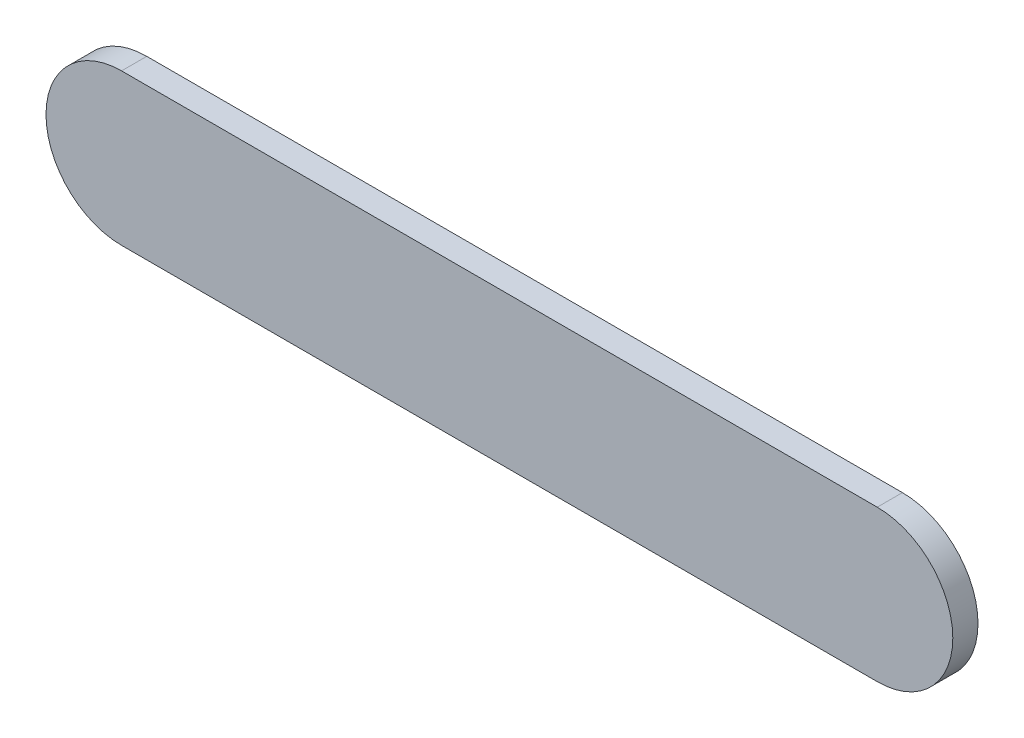
SolidWorks part; units mm, degrees
ref_plane "Front Plane" through (0, 0, 0) normal (0, 0, 1) x (1, 0, 0)
ref_plane "Top Plane" through (0, 0, 0) normal (0, 1, 0) x (1, 0, 0)
ref_plane "Right Plane" through (0, 0, 0) normal (1, 0, 0) x (0, 0, -1)
sketch "Sketch1" plane through (0, 0, 0) normal (0, 0, 1) x (1, 0, 0)
  line L0 (0, 0) -> (150, 0) construction
  line L1 (0, 15) -> (150, 15)
  line L2 (0, -15) -> (150, -15)
  arc A0 (0, 15) -> (0, -15) centre (0, 0) ccw
  arc A1 (150, -15) -> (150, 15) centre (150, 0) ccw
  point P3 (75, 0)
  dimension "D1" = 30
  dimension "D2" = 150
extrude "Boss-Extrude1" add sketch "Sketch1" along normal blind 5
